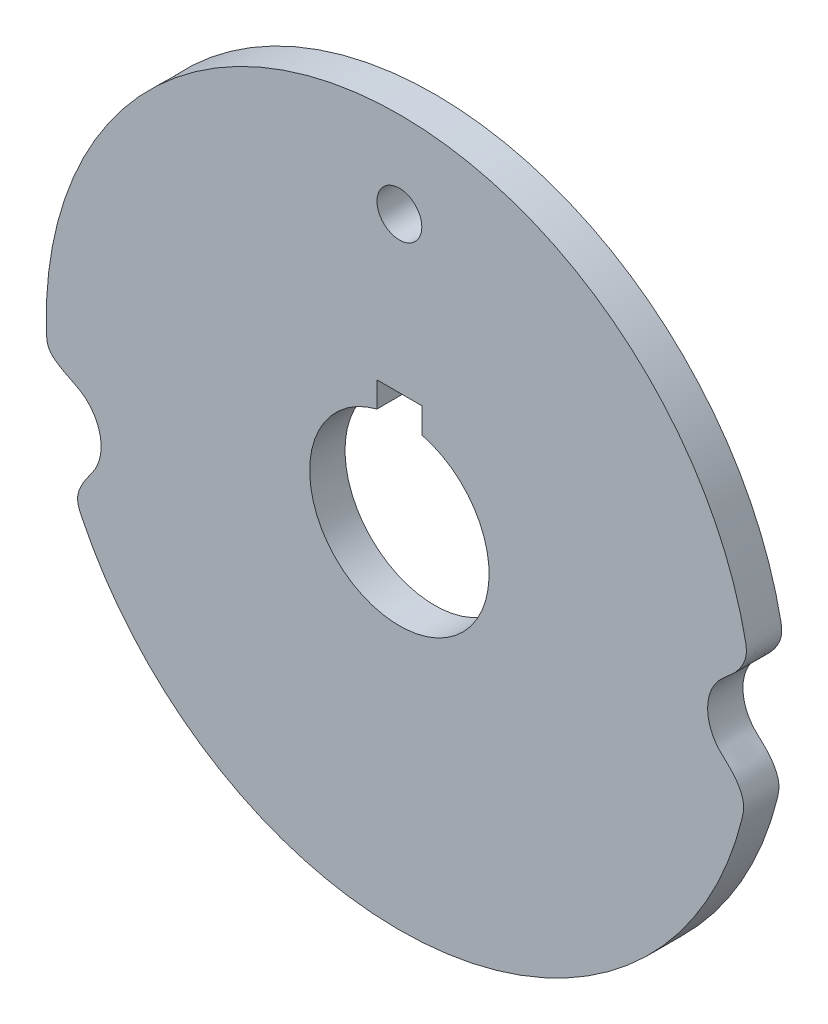
SolidWorks part; units mm, degrees
ref_plane "Alzado" through (0, 0, 0) normal (0, 0, 1) x (1, 0, 0)
ref_plane "Planta" through (0, 0, 0) normal (0, 1, 0) x (1, 0, 0)
ref_plane "Vista lateral" through (0, 0, 0) normal (1, 0, 0) x (0, 0, -1)
sketch "Croquis1" plane through (0, 0, 0) normal (0, 0, 1) x (1, 0, 0)
  line L0 (0, 50) -> (0, 37.79) construction
  line L2 (3.175, 12.2967) -> (3.175, 15.875)
  line L3 (3.175, 15.875) -> (-3.175, 15.875)
  line L4 (-3.175, 12.2967) -> (-3.175, 15.875)
  arc A0 (49.5968, 6.3372) -> (-49.6874, -5.582) centre (0, 0) ccw construction
  arc A1 (-3.175, 12.2967) -> (3.175, 12.2967) centre (0, 0) ccw
  circle A2 centre (0, 37.79) radius 3.175
  arc A3 (49.5968, 6.3372) -> (49.5968, -6.3372) centre (50, 0) ccw construction
  arc A4 (-46.6875, -17.8962) -> (-49.6874, -5.582) centre (-48.5793, -11.8345) ccw construction
  arc A5 (-46.6875, -17.8962) -> (49.5968, -6.3372) centre (0, 0) ccw construction
  spline S0 degree 3 poles (-46.6875, -17.8962) (-23.5491, -78.2598) (35.0435, -64.8701) (48.4463, -12.3674) (48.6605, -11.5283) (49.0454, -9.839) (47.2768, -6.9405) (45.8538, -5.8914) (45.2739, -5.2482) (42.9068, -2.6228) (42.9773, 0.9114) (45.4471, 3.4405) (46.0521, 4.06) (47.5157, 5.0516) (49.3984, 7.8773) (49.0812, 9.5806) (48.9006, 10.4276) (32.0505, 89.4468) (-48.3804, 81.7759) (-49.9901, 0.9961) (-50.0331, -1.1609) (-49.9373, -3.3578) (-49.6874, -5.582) knots 0.520202 0.520202 0.520202 0.520202 0.891107 0.891107 0.891107 0.90276 0.914412 0.926065 0.926065 0.926065 0.965043 0.965043 0.965043 0.976695 0.988348 1 1 1 1.445554 1.445554 1.445554 1.473509 1.473509 1.473509 1.473509 weights 0.75307 0.426403 0.508713 1 1 1 1 1 1 0.819475 0.819475 1 1 1 1 1 1 0.409837 0.409837 1 0.962971 0.928266 0.895884 construction
  spline S1 degree 3 poles (-44.9418, -21.9142) (-18.1526, -76.8538) (36.0317, -60.9987) (48.4463, -12.3674) (48.6605, -11.5283) (49.0454, -9.839) (47.2768, -6.9405) (45.8538, -5.8914) (45.2739, -5.2482) (42.9068, -2.6228) (42.9773, 0.9114) (45.4471, 3.4405) (46.0521, 4.06) (47.5157, 5.0516) (49.3984, 7.8773) (49.0812, 9.5806) (48.9006, 10.4276) (32.0505, 89.4468) (-48.3804, 81.7759) (-49.9901, 0.9961) (-50.0074, 0.1273) (-50.0022, -0.7483) (-49.9734, -1.6301) (-49.9484, -2.3959) (-49.8633, -3.9262) (-47.1851, -5.4929) (-45.7504, -6.0981) (-45.1088, -6.5168) (-42.1485, -8.4487) (-41.3118, -11.8832) (-43.0519, -14.9603) (-43.446, -15.6572) (-44.4979, -16.9021) (-45.96, -19.7383) (-45.2928, -21.1945) (-44.9418, -21.9142) (-18.1526, -76.8538) (36.0317, -60.9987) knots -0.010091 0 0 0 0.349446 0.349446 0.349446 0.360869 0.372292 0.383715 0.383715 0.383715 0.421925 0.421925 0.421925 0.433348 0.444771 0.456193 0.456193 0.456193 0.892968 0.892968 0.892968 0.904256 0.904256 0.904256 0.913911 0.923566 0.933221 0.933221 0.933221 0.969728 0.969728 0.969728 0.979819 0.989909 1 1 1 1.349446 1.349446 1.349446 weights 0.716786 0.433429 0.527834 1 1 1 1 1 1 0.819475 0.819475 1 1 1 1 1 1 0.409837 0.409837 1 0.984749 0.969892 0.955429 0.955429 0.955429 0.955429 0.955429 0.955429 0.78295 0.78295 0.955429 0.955429 0.955429 0.955429 0.955429 0.716786 0.433429 0.527834 only from (-44.9418, -21.9142) to (-44.9418, -21.9142)
  point P4 (0, 12.7)
  dimension "D1" = 100
  dimension "D2" = 25.4
  dimension "D5" = 6.35
  dimension "D6" = 12.7
  dimension "D8" = 12.7
  dimension "D3" = 6.35
  dimension "D4" = 12.21
extrude "Saliente-Extruir1" add sketch "Croquis1" along normal blind 5
